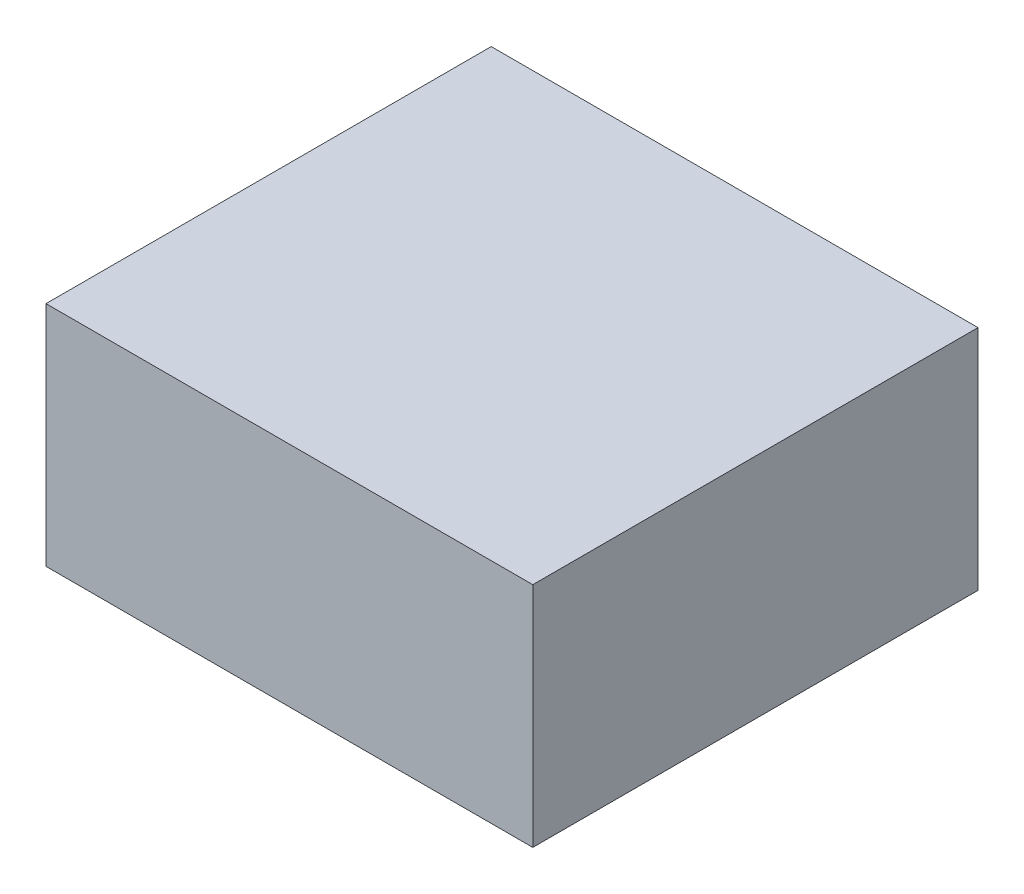
SolidWorks part; units mm, degrees
ref_plane "Piano frontale" through (0, 0, 0) normal (0, 0, 1) x (1, 0, 0)
ref_plane "Piano superiore" through (0, 0, 0) normal (0, 1, 0) x (1, 0, 0)
ref_plane "Piano destro" through (0, 0, 0) normal (1, 0, 0) x (0, 0, -1)
sketch "Schizzo1" plane through (0, 0, 0) normal (0, 1, 0) x (1, 0, 0)
  line L1 (12.3, -11.25) -> (-12.3, -11.25)
  line L2 (12.3, -11.25) -> (12.3, 11.25)
  line L3 (12.3, 11.25) -> (-12.3, 11.25)
  line L4 (-12.3, -11.25) -> (-12.3, 11.25)
  line L5 (12.3, -11.25) -> (-12.3, 11.25) construction
  line L6 (12.3, 11.25) -> (-12.3, -11.25) construction
  point P0 (0, 0)
  dimension "D1" = 22.5
  dimension "D2" = 24.6
extrude "Estrusione-Estrusione1" add sketch "Schizzo1" along normal blind 11.5
